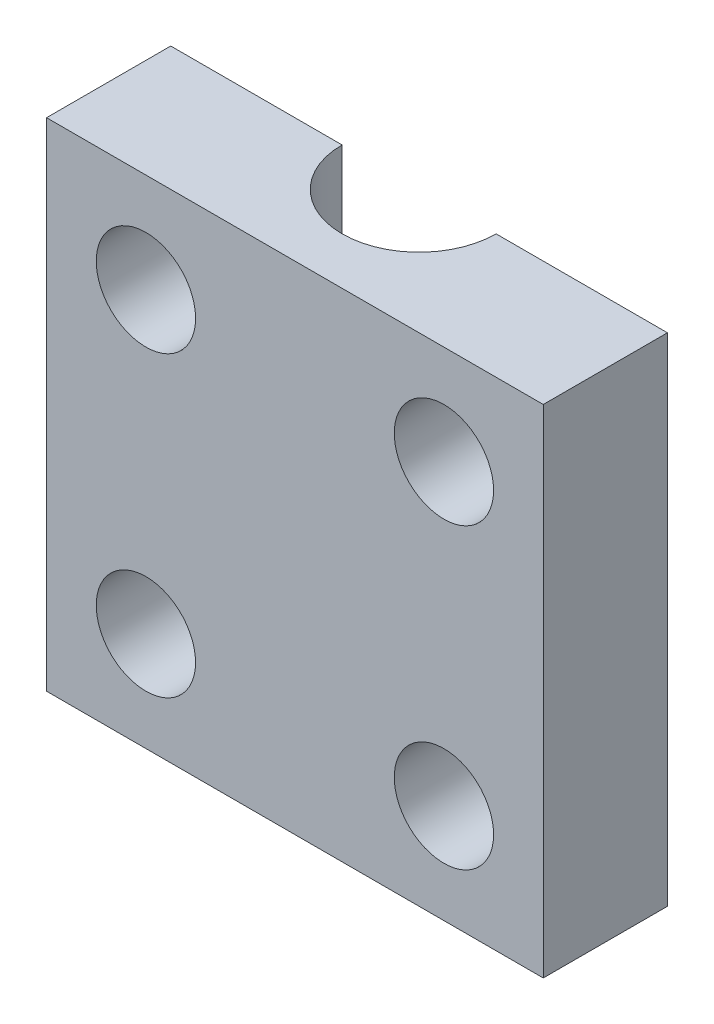
SolidWorks part; units mm, degrees
ref_plane "Front Plane" through (0, 0, 0) normal (0, 0, 1) x (1, 0, 0)
ref_plane "Top Plane" through (0, 0, 0) normal (0, 1, 0) x (1, 0, 0)
ref_plane "Right Plane" through (0, 0, 0) normal (1, 0, 0) x (0, 0, -1)
sketch "Sketch1" plane through (0, 0, 0) normal (0, 0, 1) x (1, 0, 0)
  line L1 (-10, 10) -> (10, 10)
  line L2 (-10, 10) -> (-10, -10)
  line L3 (-10, -10) -> (10, -10)
  line L4 (10, 10) -> (10, -10)
  point P4 (-10, 0)
  point P6 (0, 10)
  dimension "D1" = 20
extrude "Boss-Extrude1" add sketch "Sketch1" along normal blind 5
sketch "Sketch2" plane through (0, 10, 0) normal (0, 1, 0) x (1, 0, 0)
  line L0 (10, 0) -> (-10, 0) construction
  circle A0 centre (0, 0) radius 3.1
  arc A1 (3.1, 0) -> (-3.1, 0) centre (0, 0) ccw construction
extrude "Cut-Extrude1" cut sketch "Sketch2" against normal up to next
sketch "Sketch3" plane through (0, 0, 5) normal (0, 0, 1) x (1, 0, 0)
  line L0 (-10, 10) -> (-10, -10) construction
  line L1 (10, 10) -> (-10, 10) construction
  line L2 (-10, -10) -> (10, -10) construction
  line L3 (10, -10) -> (10, 10) construction
  circle A0 centre (-6, 6) radius 2
  circle A1 centre (-6, -6) radius 2
  circle A2 centre (6, -6) radius 2
  circle A3 centre (6, 6) radius 2
  dimension "D1" = 4
  dimension "D2" = 4
  dimension "D3" = 4
  dimension "D4" = 4
  dimension "D5" = 4
extrude "Cut-Extrude2" cut sketch "Sketch3" against normal up to next
